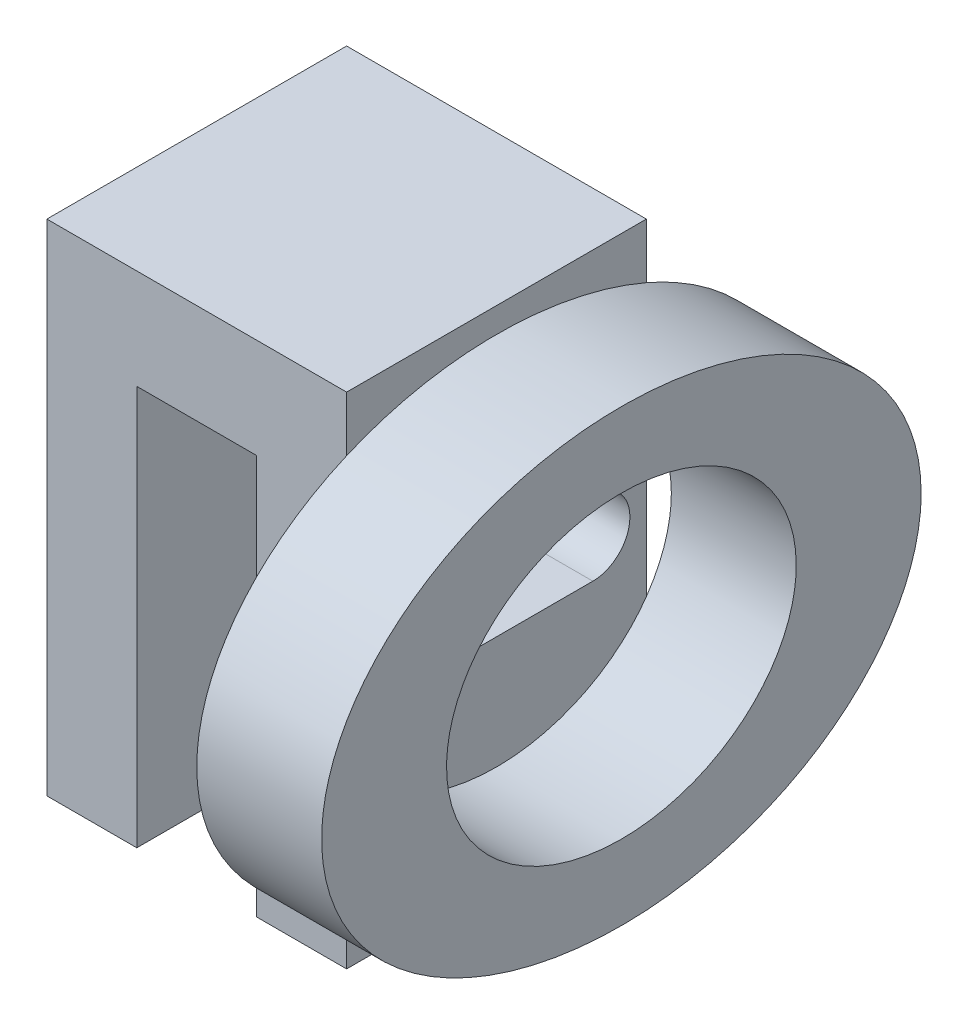
SolidWorks part; units mm, degrees
ref_plane "前视基准面" through (0, 0, 0) normal (0, 0, 1) x (1, 0, 0)
ref_plane "上视基准面" through (0, 0, 0) normal (0, 1, 0) x (1, 0, 0)
ref_plane "右视基准面" through (0, 0, 0) normal (1, 0, 0) x (0, 0, -1)
sketch "草图1" plane through (0, 0, 0) normal (0, 1, 0) x (1, 0, 0)
  line L0 (-5.1121, 4.4953) -> (-5.1121, -1.5047)
  line L1 (-5.1121, -1.5047) -> (0.8879, -1.5047)
  line L2 (0.8879, -1.5047) -> (0.8879, 4.4953)
  line L3 (0.8879, 4.4953) -> (-5.1121, 4.4953)
  dimension "D1" = 6
  dimension "D2" = 6
extrude "凸台-拉伸1" add sketch "草图1" along normal blind 10
sketch "草图2" plane through (0, 0, 1.5047) normal (0, 0, 1) x (1, 0, 0)
  line L0 (-3.3121, 0) -> (-3.3121, 8)
  line L1 (-5.1121, 0) -> (0.8879, 0) construction
  line L2 (-3.3121, 8) -> (-0.9121, 8)
  line L3 (-0.9121, 8) -> (-0.9121, 0)
  line L4 (-0.9121, 0) -> (-3.3121, 0)
  line L5 (-5.1121, 10) -> (-5.1121, 0) construction
  dimension "D1" = 8
  dimension "D2" = 2.4
  dimension "D3" = 1.8
extrude "切除-拉伸1" cut sketch "草图2" against normal blind 10
sketch "草图3" plane through (0.8879, 0, 0) normal (1, 0, 0) x (0, 0, -1)
  line L0 (-1.5047, 10) -> (4.4953, 0) construction
  line L1 (-1.5047, 0) -> (4.4953, 10) construction
  line L2 (4.4953, 10) -> (4.4953, 0) construction
  line L6 (1.4953, 9.5) -> (1.4953, 0.5) construction
  ellipse E0 centre (1.4953, 5) end of major axis (7.4953, 5) minor radius 4.5
  point P9 (1.4953, 5)
  dimension "D1" = 9
  dimension "D2" = 12
extrude "凸台-拉伸2" add sketch "草图3" along normal blind 2.5
sketch "草图4" plane through (3.3879, 0, 0) normal (1, 0, 0) x (0, 0, -1)
  line L0 (1.4953, 10) -> (1.4953, 0) construction
  line L1 (-1.5047, 10) -> (4.4953, 10) construction
  ellipse E0 centre (1.4953, 5) end of major axis (-2.0047, 5) minor radius 3
  point P2 (1.4953, 10)
  point P9 (1.4953, 5)
  dimension "D2" = 6
  dimension "D3" = 7
extrude "切除-拉伸3" cut sketch "草图4" against normal blind 2.5 contours E0
sketch "草图5" plane through (0.8879, 0, 0) normal (1, 0, 0) x (0, 0, -1)
  line L0 (-1.5047, 5) -> (4.4953, 5) construction
  line L1 (-1.5047, 6.5452) -> (-1.5047, 3.4548) construction
  line L2 (4.4953, 6.5452) -> (4.4953, 3.4548) construction
  line L3 (-0.4671, 5) -> (3.4242, 5) construction
  line L6 (-0.4671, 5.742) -> (3.4242, 5.742)
  line L7 (-0.4671, 4.258) -> (3.4242, 4.258)
  arc A2 (-0.4671, 5.742) -> (-0.4671, 4.258) centre (-0.4671, 5) ccw
  arc A3 (3.4242, 4.258) -> (3.4242, 5.742) centre (3.4242, 5) ccw
  point P6 (1.4953, 5)
  point P9 (1.4785, 5)
  point P14 (1.2388, 5)
  point P15 (-1.5047, 5)
  point P16 (0.7533, 5)
  point P17 (0.6132, 4.7296)
  point P18 (0, 0)
  point P19 (-1.5047, 5)
  point P20 (-1.5047, 5)
  point P21 (-0.4671, 5.742)
extrude "切除-拉伸4" cut sketch "草图5" against normal blind 2
